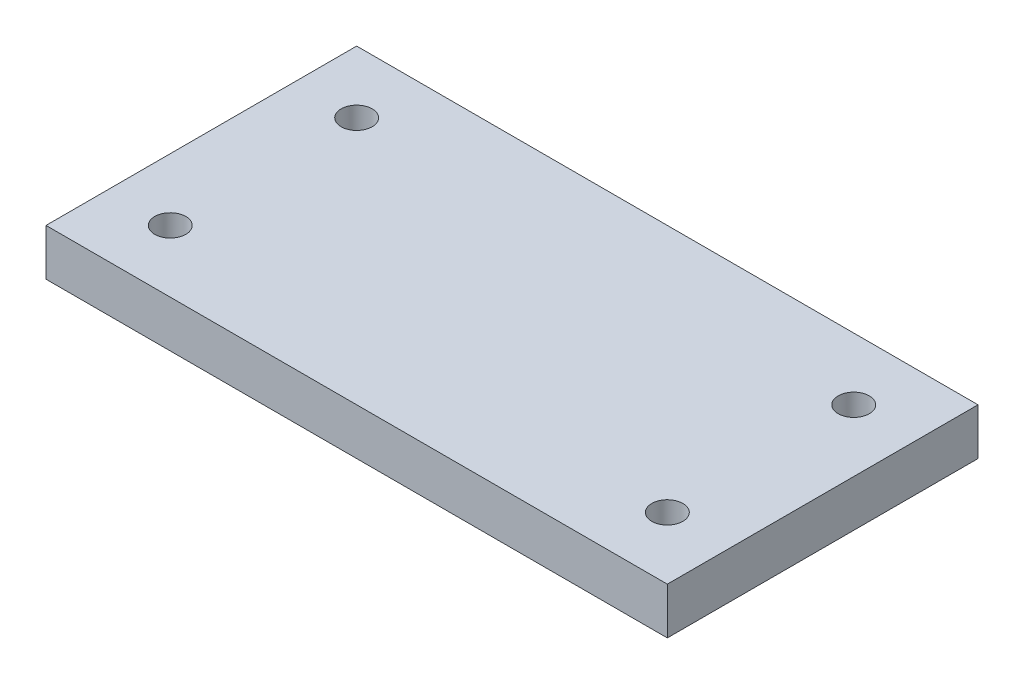
SolidWorks part; units mm, degrees
ref_plane "前视基准面" through (0, 0, 0) normal (0, 0, 1) x (1, 0, 0)
ref_plane "上视基准面" through (0, 0, 0) normal (0, 1, 0) x (1, 0, 0)
ref_plane "右视基准面" through (0, 0, 0) normal (1, 0, 0) x (0, 0, -1)
other "Configuration Table"
sketch "草图1" plane through (0, 0, 0) normal (0, 1, 0) x (1, 0, 0)
  line L1 (-100, -50) -> (100, -50)
  line L2 (-100, -50) -> (-100, 50)
  line L3 (-100, 50) -> (100, 50)
  line L4 (100, -50) -> (100, 50)
  line L5 (-100, -50) -> (100, 50) construction
  line L6 (-100, 50) -> (100, -50) construction
  point P0 (0, 0)
extrude "凸台-拉伸1" add sketch "草图1" along normal blind 15
sketch "草图2" plane through (0, 0, 0) normal (0, 1, 0) x (1, 0, 0)
  circle A0 centre (-80, -30) radius 5
  circle A1 centre (80, -30) radius 5
  circle A2 centre (-80, 30) radius 5
extrude "切除-拉伸1" cut sketch "草图2" along normal blind 30
sketch "草图3" plane through (0, 0, 0) normal (0, 1, 0) x (1, 0, 0)
  circle A0 centre (80, 30) radius 5
extrude "切除-拉伸2" cut sketch "草图3" along normal blind 30
